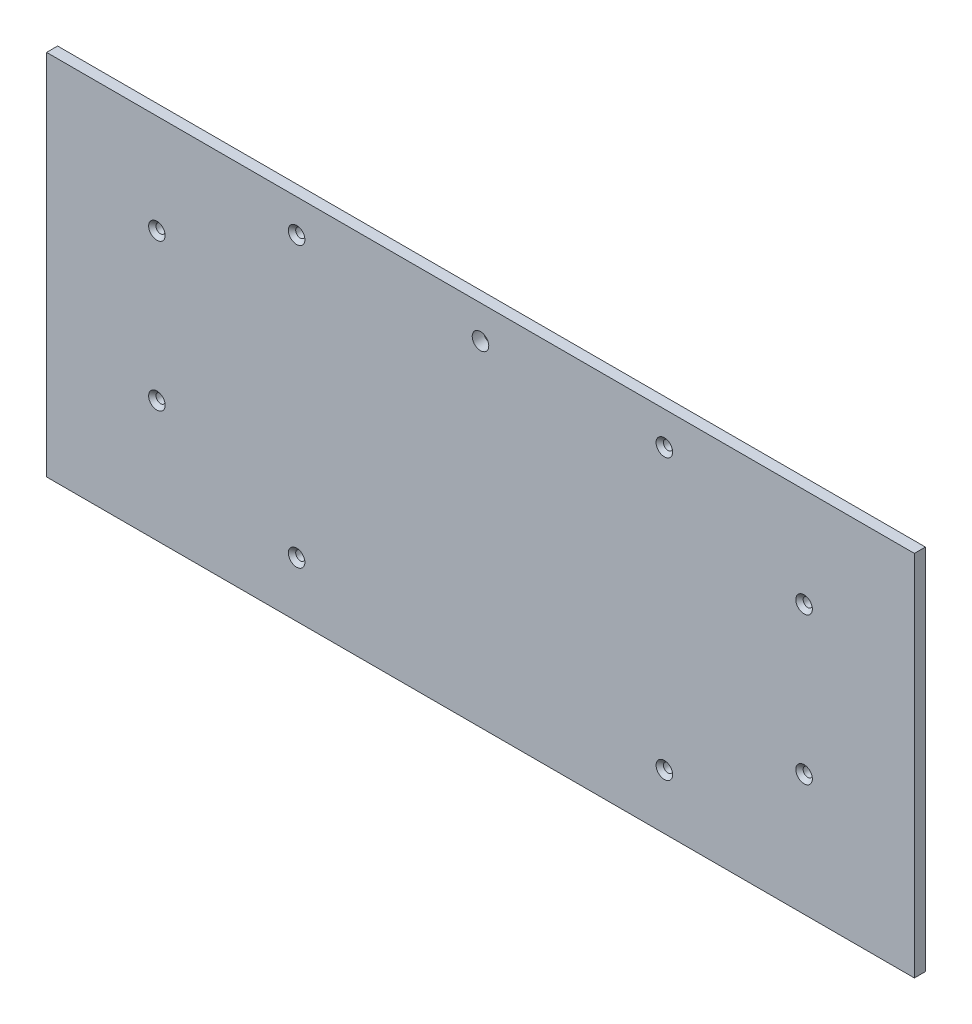
SolidWorks part; units mm, degrees
ref_plane "Plan de face" through (0, 0, 0) normal (0, 0, 1) x (1, 0, 0)
ref_plane "Plan de dessus" through (0, 0, 0) normal (0, 1, 0) x (1, 0, 0)
ref_plane "Plan de droite" through (0, 0, 0) normal (1, 0, 0) x (0, 0, -1)
sketch "Esquisse1" plane through (0, 0, 0) normal (0, 0, 1) x (1, 0, 0)
  line L1 (-236, -100) -> (236, -100)
  line L2 (-236, -100) -> (-236, 100)
  line L3 (-236, 100) -> (236, 100)
  line L4 (236, -100) -> (236, 100)
  line L5 (-236, -100) -> (236, 100) construction
  line L6 (-236, 100) -> (236, -100) construction
  point P0 (0, 0)
  dimension "D1" = 200
  dimension "D2" = 472
extrude "Boss.-Extru.1" add sketch "Esquisse1" along normal blind 6
sketch "Esquisse2" plane through (0, 0, 6) normal (0, 0, 1) x (1, 0, 0)
  line L0 (0, -100) -> (0, 100) construction
  line L1 (-236, -100) -> (236, -100) construction
  line L2 (236, 100) -> (-236, 100) construction
  line L3 (236, -100) -> (236, 100) construction
  line L4 (176, 82) -> (-176, 82) construction
  line L5 (176, 82) -> (176, -70) construction
  line L6 (176, -70) -> (-176, -70) construction
  line L7 (-176, 82) -> (-176, -70) construction
  line L8 (176, 82) -> (-176, -70) construction
  line L9 (176, -70) -> (-176, 82) construction
  line L10 (0, 6) -> (-236, 6) construction
  line L11 (-236, 100) -> (-236, -100) construction
  circle A0 centre (100, -70) radius 2.5
  circle A1 centre (-100, -70) radius 2.5
  circle A2 centre (-100, 82) radius 2.5
  circle A3 centre (100, 82) radius 2.5
  circle A4 centre (176, -34) radius 2.5
  circle A5 centre (176, 46) radius 2.5
  circle A6 centre (-176, 46) radius 2.5
  circle A7 centre (-176, -34) radius 2.5
  point P6 (0, 6)
  dimension "D4" = 5
  dimension "D1" = 30
  dimension "D2" = 18
  dimension "D3" = 60
  dimension "D5" = 200
  dimension "D6" = 80
extrude "Enlèv. mat.-Extru.1" cut sketch "Esquisse2" against normal through all
chamfer "Chanfrein1" distance 2 angle 45 8 edges at (102.5, 82, 6) (-97.5, 82, 6) (-97.5, -70, 6) (102.5, -70, 6) (-173.5, -34, 6) (-173.5, 46, 6) (178.5, 46, 6) (178.5, -34, 6)
sketch "Esquisse4" plane through (0, 0, 6) normal (0, 0, 1) x (1, 0, 0)
  line L0 (-100, 82) -> (100, 82) construction
  circle A0 centre (0, 82) radius 4.5
  dimension "D1" = 9
extrude "Enlèv. mat.-Extru.2" cut sketch "Esquisse4" against normal through all
